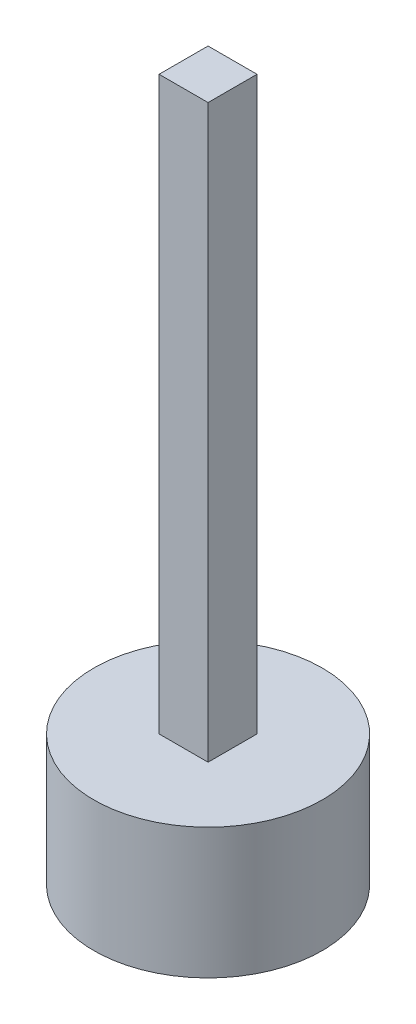
SolidWorks part; units mm, degrees
ref_plane "Front Plane" through (0, 0, 0) normal (0, 0, 1) x (1, 0, 0)
ref_plane "Top Plane" through (0, 0, 0) normal (0, 1, 0) x (1, 0, 0)
ref_plane "Right Plane" through (0, 0, 0) normal (1, 0, 0) x (0, 0, -1)
sketch "Sketch1" plane through (0, 0, 0) normal (0, 1, 0) x (1, 0, 0)
  line L1 (15, 0) -> (-15, 0)
  line L2 (15, 0) -> (15, 30)
  line L3 (15, 30) -> (-15, 30)
  line L4 (-15, 0) -> (-15, 30)
  dimension "D1" = 30
extrude "Boss-Extrude1" add sketch "Sketch1" against normal blind 350
sketch "Sketch2" plane through (0, -350, 0) normal (0, -1, 0) x (1, 0, 0)
  line L0 (0, 0) -> (0, -30)
  line L1 (-15, 0) -> (15, 0) construction
  line L2 (15, -30) -> (-15, -30) construction
  line L3 (-15, -15) -> (15, -15)
  line L4 (-15, -30) -> (-15, 0) construction
  line L5 (15, 0) -> (15, -30) construction
  circle A0 centre (0, -15) radius 70
  dimension "D1" = 140
extrude "Boss-Extrude2" add sketch "Sketch2" along normal blind 80 contours A0
sketch "Sketch3" plane through (0, -430, 0) normal (0, -1, 0) x (1, 0, 0)
  circle A0 centre (0, -15) radius 70 construction
  point P0 (0, -15)
